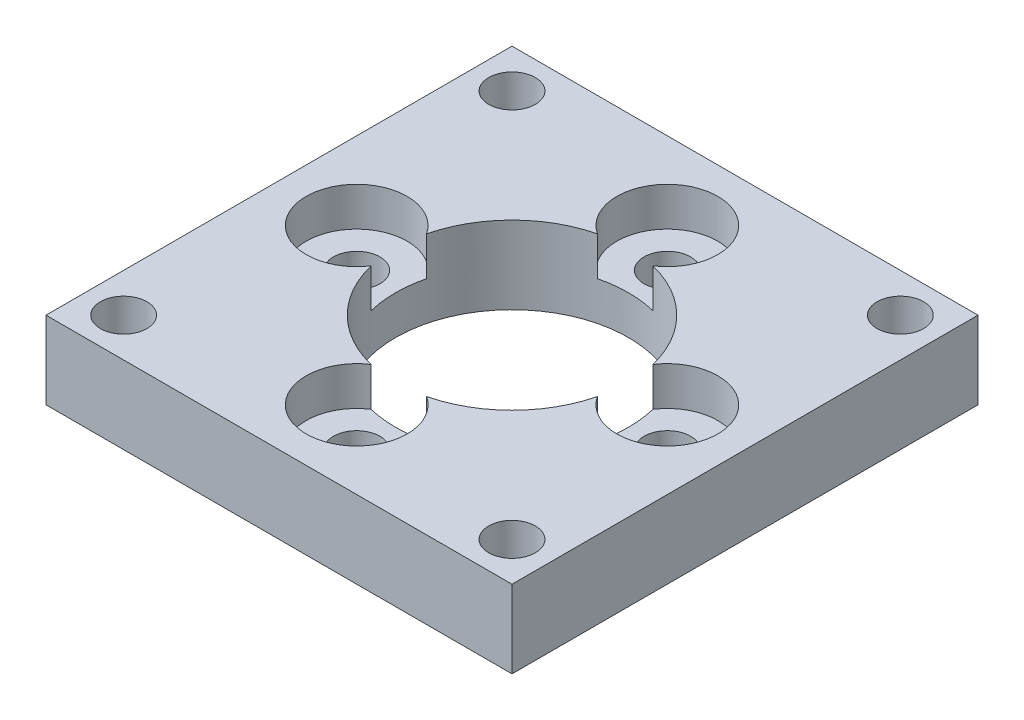
SolidWorks part; units mm, degrees
ref_plane "Front Plane" through (0, 0, 0) normal (0, 0, 1) x (1, 0, 0)
ref_plane "Top Plane" through (0, 0, 0) normal (0, 1, 0) x (1, 0, 0)
ref_plane "Right Plane" through (0, 0, 0) normal (1, 0, 0) x (0, 0, -1)
sketch "Sketch1" plane through (0, 0, 0) normal (0, 1, 0) x (1, 0, 0)
  line L0 (53.57, 53.57) -> (6.43, 6.43) construction
  line L1 (0, 0) -> (60, 0)
  line L2 (0, 0) -> (0, 60)
  line L3 (0, 60) -> (60, 60)
  line L4 (60, 0) -> (60, 60)
  circle A4 centre (30, 30) radius 15
  point P7 (30, 30)
  dimension "D10" = 30
  dimension "D6" = 30
  dimension "D7" = 30
  dimension "D8" = 60
  dimension "D9" = 60
extrude "Boss-Extrude1" add sketch "Sketch1" along normal blind 10
sketch "Sketch2" plane through (0, 10, 0) normal (0, 1, 0) x (1, 0, 0)
  circle A0 centre (30, 30) radius 20
  circle A1 centre (30, 50) radius 3
  circle A2 centre (50, 30) radius 3
  circle A3 centre (30, 10) radius 3
  circle A4 centre (10, 30) radius 3
  point P14 (30, 30)
  dimension "D1" = 40
  dimension "D3" = 6
  dimension "D2" = 4
extrude "Cut-Extrude1" cut sketch "Sketch2" against normal blind 10 contours A1 | A4 | A3 | A2
sketch "Sketch3" plane through (0, 10, 0) normal (0, 1, 0) x (1, 0, 0)
  circle A0 centre (30, 30) radius 20
  circle A1 centre (30, 50) radius 6.5
  circle A2 centre (50, 30) radius 6.5
  circle A3 centre (30, 10) radius 6.5
  circle A4 centre (10, 30) radius 6.5
  point P15 (30, 30)
  dimension "D1" = 13
  dimension "D3" = 40
  dimension "D4" = 20
  dimension "D2" = 4
extrude "Cut-Extrude2" cut sketch "Sketch3" against normal blind 5 contours A4 | A3 | A2 | A1
sketch "Sketch4" plane through (0, 0, 0) normal (0, -1, 0) x (1, 0, 0)
  line L1 (5, -5) -> (55, -5)
  line L2 (5, -5) -> (5, -55)
  line L3 (5, -55) -> (55, -55)
  line L4 (55, -5) -> (55, -55)
  circle A0 centre (30, -30) radius 15 construction
  circle A1 centre (5, -5) radius 3
  circle A2 centre (55, -5) radius 3
  circle A3 centre (55, -55) radius 3
  circle A4 centre (5, -55) radius 3
  dimension "D3" = 25
  dimension "D4" = 25
  dimension "D5" = 6
  dimension "D6" = 6
  dimension "D7" = 6
  dimension "D8" = 6
  dimension "D1" = 50
  dimension "D2" = 50
extrude "Cut-Extrude3" cut sketch "Sketch4" against normal blind 10 contours A1 | A2 | A3 | A4
